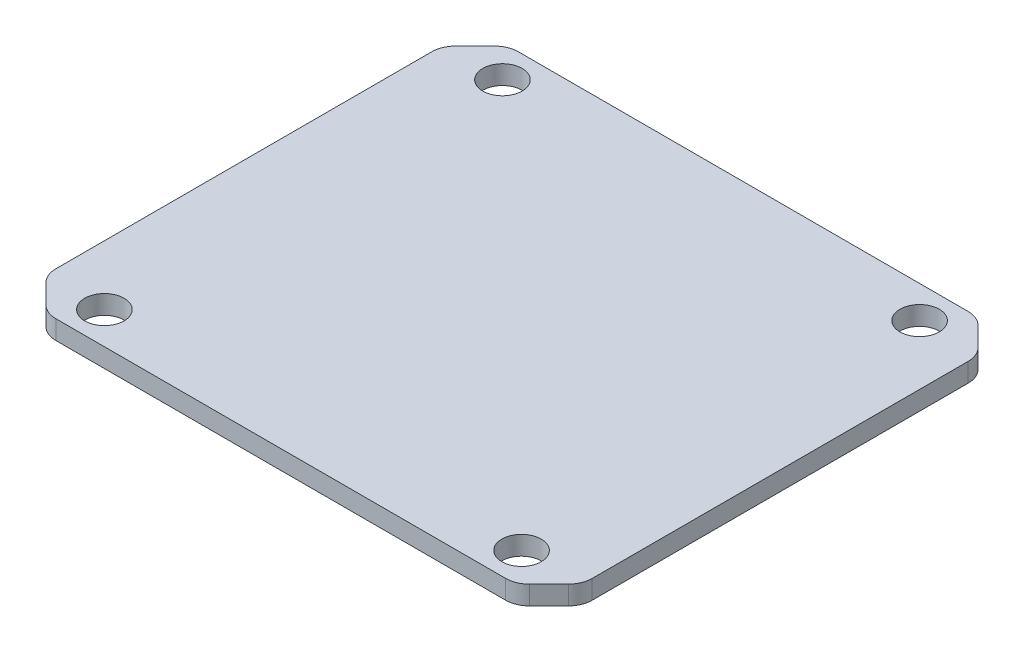
SolidWorks part; units mm, degrees
ref_plane "Front Plane" through (0, 0, 0) normal (0, 0, 1) x (1, 0, 0)
ref_plane "Top Plane" through (0, 0, 0) normal (0, 1, 0) x (1, 0, 0)
ref_plane "Right Plane" through (0, 0, 0) normal (1, 0, 0) x (0, 0, -1)
sketch "Sketch1" plane through (0, 0, 0) normal (0, 1, 0) x (1, 0, 0)
  line L1 (-22.5, -19.4) -> (22.5, -19.4)
  line L2 (-22.5, -19.4) -> (-22.5, 19.4)
  line L3 (-22.5, 19.4) -> (22.5, 19.4)
  line L4 (22.5, -19.4) -> (22.5, 19.4)
  line L5 (-22.5, -19.4) -> (22.5, 19.4) construction
  line L6 (-22.5, 19.4) -> (22.5, -19.4) construction
  point P0 (0, 0)
  dimension "D1" = 45
  dimension "D2" = 38.8
extrude "Boss-Extrude1" add sketch "Sketch1" along normal mid plane 1.5875
sketch "Sketch2" plane through (0, 0.7937, 0) normal (0, 1, 0) x (1, 0, 0)
  line L1 (-17.5, -16.7) -> (17.5, -16.7) construction
  line L2 (-17.5, -16.7) -> (-17.5, 16.7) construction
  line L3 (-17.5, 16.7) -> (17.5, 16.7) construction
  line L4 (17.5, -16.7) -> (17.5, 16.7) construction
  line L5 (-17.5, -16.7) -> (17.5, 16.7) construction
  line L6 (-17.5, 16.7) -> (17.5, -16.7) construction
  circle A0 centre (-17.5, 16.7) radius 1.65
  circle A1 centre (17.5, 16.7) radius 1.65
  circle A2 centre (17.5, -16.7) radius 1.65
  circle A3 centre (-17.5, -16.7) radius 1.65
  point P0 (0, 0)
  dimension "D1" = 3.3
  dimension "D2" = 33.4
  dimension "D3" = 35
extrude "Cut-Extrude1" cut sketch "Sketch2" against normal through all both and the other way through all
chamfer "Chamfer1" distance 2.8 angle 45 4 edges at (-22.5, 0, 19.4) (-22.5, 0, -19.4) (22.5, 0, -19.4) (22.5, 0, 19.4)
fillet "Fillet1" radius 2 8 edges at (-22.5, 0, -16.6) (-19.7, 0, -19.4) (19.7, 0, -19.4) (22.5, 0, -16.6) (22.5, 0, 16.6) (19.7, 0, 19.4) (-22.5, 0, 16.6) (-19.7, 0, 19.4)
